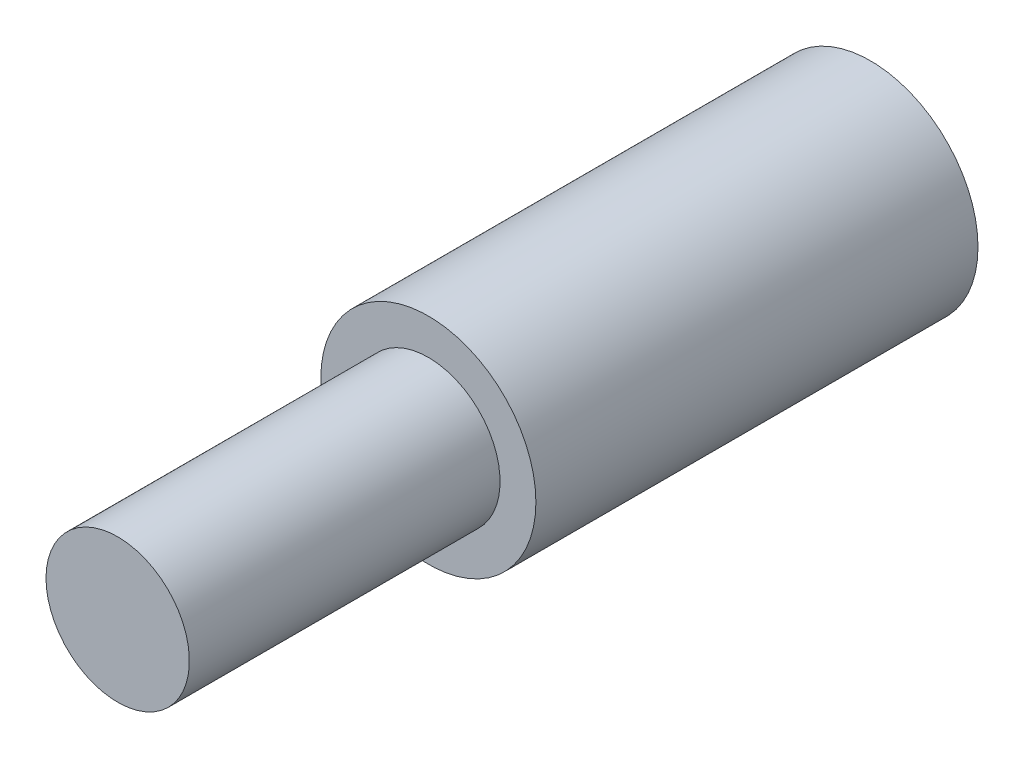
SolidWorks part; units mm, degrees
ref_plane "Alzado" through (0, 0, 0) normal (0, 0, 1) x (1, 0, 0)
ref_plane "Planta" through (0, 0, 0) normal (0, 1, 0) x (1, 0, 0)
ref_plane "Vista lateral" through (0, 0, 0) normal (1, 0, 0) x (0, 0, -1)
sketch "Croquis1" plane through (0, 0, 0) normal (0, 0, 1) x (1, 0, 0)
  circle A0 centre (0, 0) radius 9
  dimension "D1" = 18
extrude "Saliente-Extruir1" add sketch "Croquis1" along normal blind 37
sketch "Croquis2" plane through (0, 0, 37) normal (0, 0, 1) x (1, 0, 0)
  circle A0 centre (0, 0) radius 6
  dimension "D1" = 12
extrude "Saliente-Extruir2" add sketch "Croquis2" along normal blind 26
